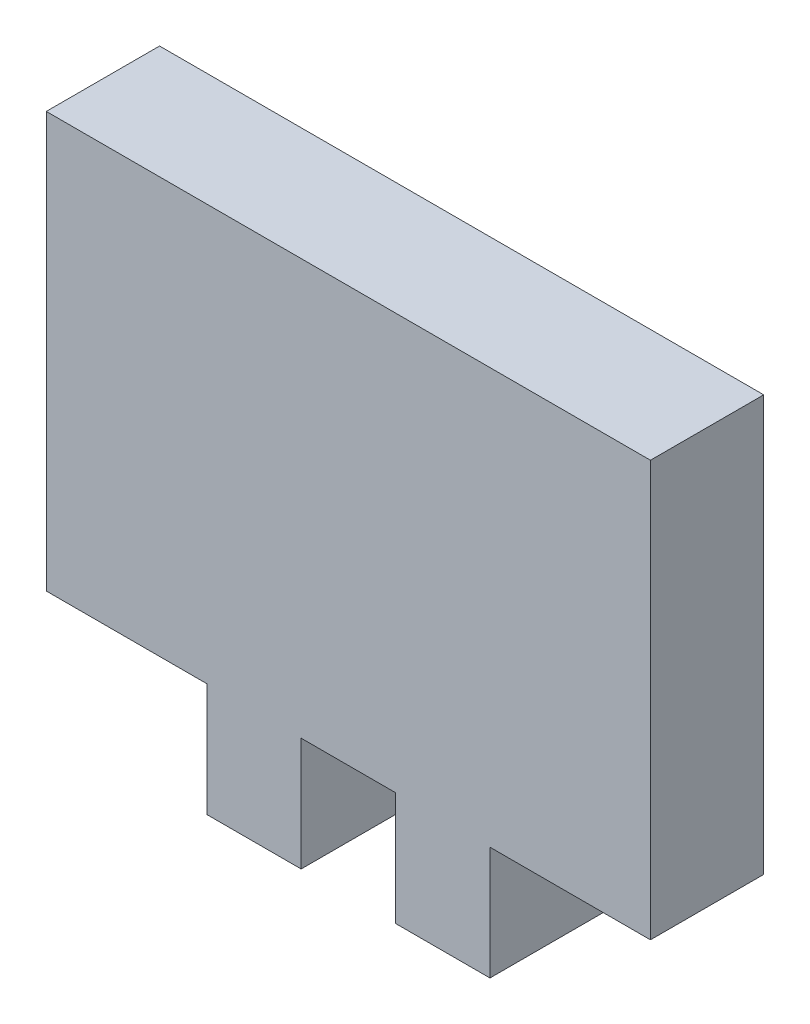
SolidWorks part; units mm, degrees
ref_plane "Front Plane" through (0, 0, 0) normal (0, 0, 1) x (1, 0, 0)
ref_plane "Top Plane" through (0, 0, 0) normal (0, 1, 0) x (1, 0, 0)
ref_plane "Right Plane" through (0, 0, 0) normal (1, 0, 0) x (0, 0, -1)
sketch "Sketch1" plane through (0, 0, 0) normal (0, 0, 1) x (1, 0, 0)
  line L0 (0, 0) -> (8.5, 0)
  line L1 (8.5, 0) -> (8.5, -6)
  line L2 (8.5, -6) -> (13.5, -6)
  line L3 (13.5, -6) -> (13.5, 0)
  line L4 (13.5, 0) -> (18.5, 0)
  line L5 (18.5, 0) -> (18.5, -6)
  line L6 (18.5, -6) -> (23.5, -6)
  line L7 (23.5, -6) -> (23.5, 0)
  line L8 (23.5, 0) -> (32, 0)
  line L9 (32, 0) -> (32, 22)
  line L10 (32, 22) -> (0, 22)
  line L11 (0, 22) -> (0, 0)
  dimension "D1" = 5
  dimension "D2" = 5
  dimension "D3" = 6
  dimension "D4" = 32
  dimension "D5" = 22
extrude "Boss-Extrude1" add sketch "Sketch1" along normal blind 6
